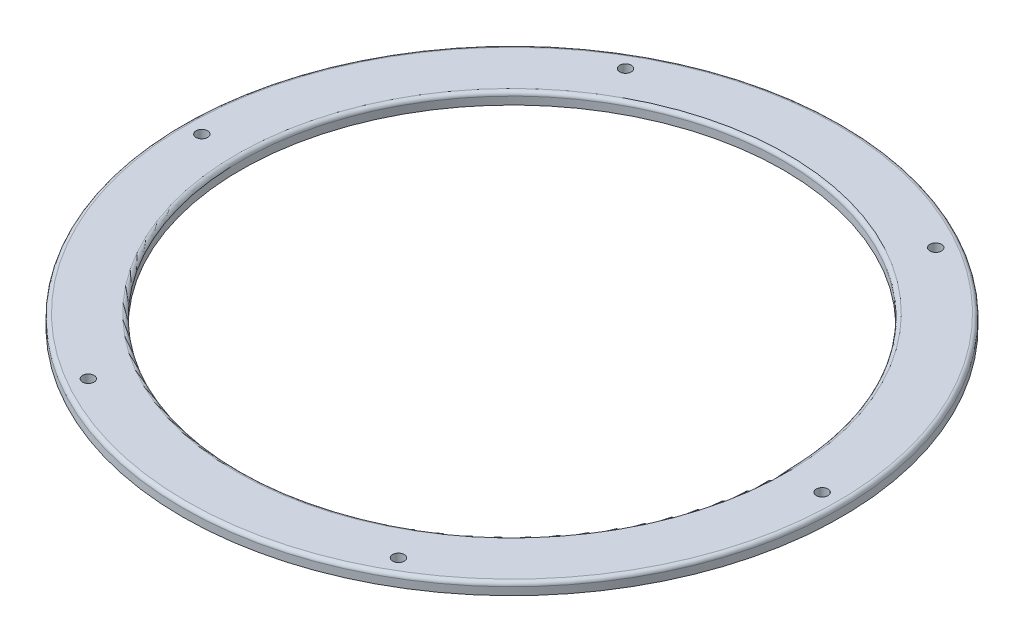
SolidWorks part; units mm, degrees
ref_plane "Plan de face" through (0, 0, 0) normal (0, 0, 1) x (1, 0, 0)
ref_plane "Plan de dessus" through (0, 0, 0) normal (0, 1, 0) x (1, 0, 0)
ref_plane "Plan de droite" through (0, 0, 0) normal (1, 0, 0) x (0, 0, -1)
sketch "Esquisse1" plane through (0, 0, 0) normal (0, 1, 0) x (1, 0, 0)
  circle A0 centre (0, 0) radius 85
  dimension "D1" = 170
extrude "Boss.-Extru.1" add sketch "Esquisse1" along normal blind 3
sketch "Esquisse2" plane through (0, 3, 0) normal (0, 1, 0) x (1, 0, 0)
  circle A0 centre (0, 0) radius 70
  dimension "D1" = 140
extrude "Enlèv. mat.-Extru.1" cut sketch "Esquisse2" against normal blind 3
sketch "Esquisse3" plane through (0, 3, 0) normal (0, 1, 0) x (1, 0, 0)
  circle A0 centre (80, 0) radius 1.5
  dimension "D2" = 3
  dimension "D1" = 80
extrude "Enlèv. mat.-Extru.2" cut sketch "Esquisse3" against normal blind 3
sketch "Esquisse4" plane through (0, 0, 0) normal (1, 0, 0) x (0, 0, -1)
  line L0 (0, 0) -> (0, 33.1256) construction
pattern_circular "Répétition circulaire1" count 6 over 360 about axis through (0, 0, 0) along (0, 1, 0) of "Enlèv. mat.-Extru.2"
fillet "Congé1" radius 1 2 edges at (0, 3, 85) (0, 3, 70)
